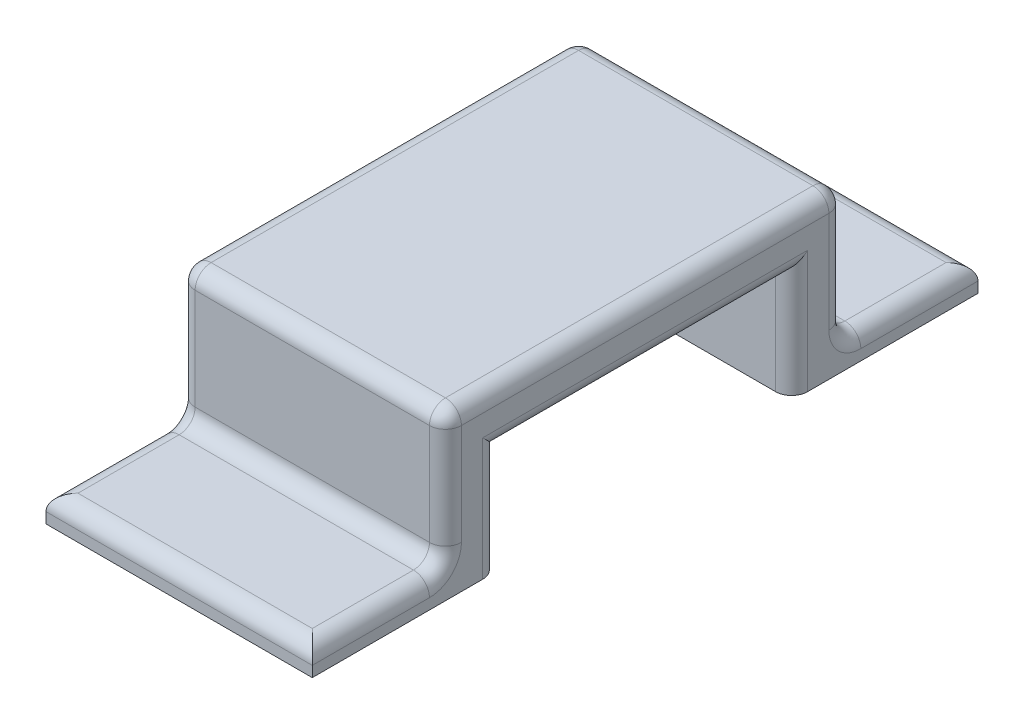
SolidWorks part; units mm, degrees
ref_plane "Front" through (0, 0, 0) normal (0, 0, 1) x (1, 0, 0)
ref_plane "Top" through (0, 0, 0) normal (0, 1, 0) x (1, 0, 0)
ref_plane "Right" through (0, 0, 0) normal (1, 0, 0) x (0, 0, -1)
sketch "Sketch2" plane through (0, 0, 0) normal (1, 0, 0) x (0, 0, -1)
  line L0 (-15.875, 1.27) -> (-6.985, 1.27)
  line L1 (-6.985, 1.27) -> (-6.985, 6.35)
  line L2 (-6.985, 6.35) -> (6.985, 6.35)
  line L3 (6.985, 6.35) -> (6.985, 1.27)
  line L4 (6.985, 1.27) -> (15.875, 1.27)
  line L5 (15.875, 1.27) -> (15.875, 2.54)
  line L6 (15.875, 2.54) -> (9.525, 2.54)
  line L7 (9.525, 2.54) -> (9.525, 8.89)
  line L8 (9.525, 8.89) -> (-9.525, 8.89)
  line L9 (-9.525, 8.89) -> (-9.525, 2.54)
  line L10 (-9.525, 2.54) -> (-15.875, 2.54)
  line L11 (-15.875, 2.54) -> (-15.875, 1.27)
  line L12 (0, 8.89) -> (0, 6.35) construction
  point P14 (0, 0)
  point P15 (0, 0)
  point P16 (0, 0)
  point P17 (0, 0)
  point P18 (0, 0)
  point P19 (0, 0)
  point P22 (0, 0)
  point P23 (0, 0)
  dimension "D1" = 1.27
  dimension "D2" = 7.62
  dimension "D3" = 2.54
  dimension "D4" = 19.05
  dimension "D5" = 2.54
  dimension "D6" = 6.35
extrude "Boss-Extrude1" add sketch "Sketch2" along normal mid plane 12.7
fillet "Fillet1" radius 0.762 22 edges at (6.35, 2.54, -12.7) (6.35, 5.715, 9.525) (-6.35, 2.54, 12.7) (-6.35, 2.54, -12.7) (0, 2.54, -15.875) (6.35, 3.81, 6.985) (6.35, 3.81, -6.985) (6.35, 6.35, 0) (6.35, 5.715, -9.525) (6.35, 2.54, 12.7) (0, 2.54, 15.875) (-6.35, 3.81, 6.985) (-6.35, 3.81, -6.985) (-6.35, 6.35, 0) (-6.35, 5.715, 9.525) (-6.35, 5.715, -9.525) (0, 2.54, -9.525) (0, 2.54, 9.525) (0, 8.89, 9.525) (6.35, 8.89, 0) (0, 8.89, -9.525) (-6.35, 8.89, 0)
